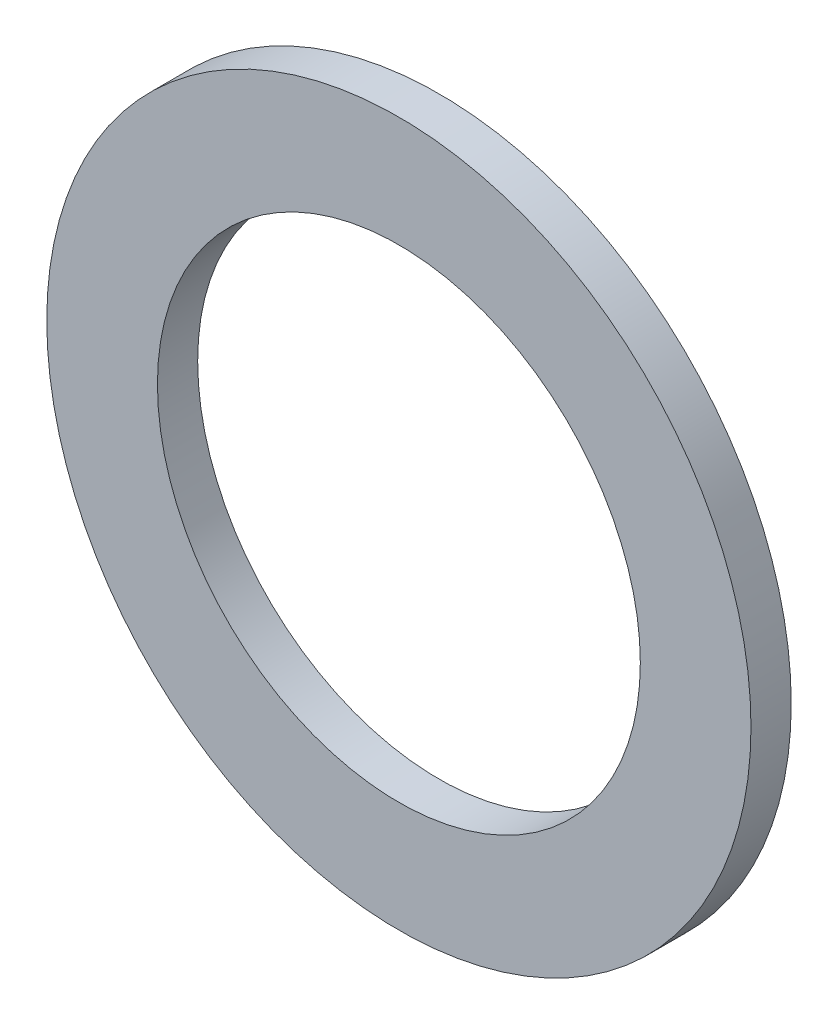
SolidWorks part; units mm, degrees
ref_plane "Front Plane" through (0, 0, 0) normal (0, 0, 1) x (1, 0, 0)
ref_plane "Top Plane" through (0, 0, 0) normal (0, 1, 0) x (1, 0, 0)
ref_plane "Right Plane" through (0, 0, 0) normal (1, 0, 0) x (0, 0, -1)
sketch "Sketch1" plane through (0, 0, 0) normal (0, 0, 1) x (1, 0, 0)
  circle A0 centre (0, 0) radius 6
  circle A1 centre (0, 0) radius 8.75
  dimension "D1" = 12
  dimension "D2" = 17.5
extrude "Boss-Extrude1" add sketch "Sketch1" against normal blind 1
